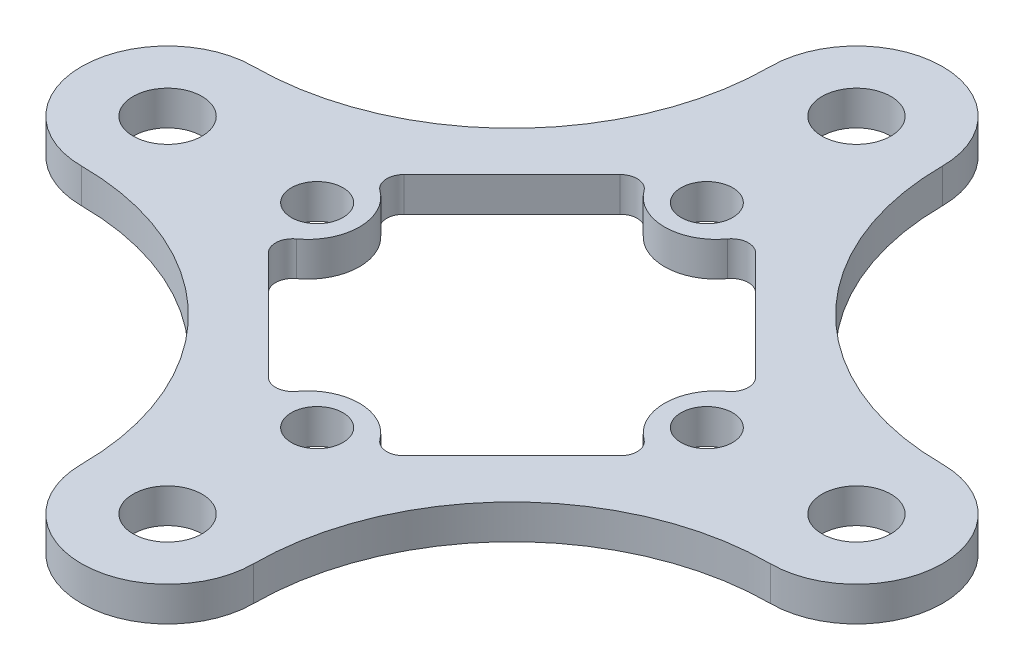
SolidWorks part; units mm, degrees
ref_plane "Front Plane" through (0, 0, 0) normal (0, 0, 1) x (1, 0, 0)
ref_plane "Top Plane" through (0, 0, 0) normal (0, 1, 0) x (1, 0, 0)
ref_plane "Right Plane" through (0, 0, 0) normal (1, 0, 0) x (0, 0, -1)
sketch "Sketch1" plane through (0, 0, 0) normal (0, 1, 0) x (1, 0, 0)
  line L0 (0, 25.1487) -> (0, -24.8633) construction
  line L1 (-28.5376, 0) -> (32.8182, 0) construction
  line L4 (0, 25) -> (0, 0)
  line L5 (0, 0) -> (25, 0)
  circle A0 centre (0, 0) radius 20 construction
  circle A6 centre (0, 20) radius 5 construction
  circle A7 centre (20, 0) radius 5 construction
  arc A8 (5, 20) -> (0, 25) centre (0, 20) ccw
  arc A10 (20, 5) -> (25, 0) centre (20, 0) cw
  arc A12 (5, 20) -> (20, 5) centre (20, 20) ccw
  point P8 (0.326, 0)
  point P17 (0, -0.3063)
  dimension "D1" = 40
  dimension "D2" = 10
extrude "Boss-Extrude1" add sketch "Sketch1" along normal blind 2
pattern_circular "CirPattern1" count 4 over 360 about axis through (0, 0, 0) along (0, 1, 0) of "Boss-Extrude1"
sketch "Sketch2" plane through (0, 2, 0) normal (0, 1, 0) x (1, 0, 0)
  line L0 (0, 26.7191) -> (0, -26.0296) construction
  line L1 (-31.2099, 0) -> (38.8403, 0) construction
  line L2 (0, 11.3137) -> (11.3137, 0) construction
  circle A0 centre (0, 11.3137) radius 1.5
  circle A1 centre (0, 20) radius 2
  circle A2 centre (0, 0) radius 11.3137 construction
  circle A3 centre (0, 0) radius 20 construction
  circle A4 centre (11.3137, 0) radius 1.5
  circle A5 centre (20, 0) radius 2
  circle A6 centre (0, -11.3137) radius 1.5
  circle A7 centre (0, -20) radius 2
  circle A8 centre (-11.3137, 0) radius 1.5
  circle A9 centre (-20, 0) radius 2
  point P28 (0, 0)
  dimension "D2" = 3
  dimension "D3" = 4
  dimension "D4" = 40
  dimension "D1" = 16
  dimension "D5" = 4
extrude "Cut-Extrude1" cut sketch "Sketch2" against normal blind 2
sketch "Sketch3" plane through (0, 2, 0) normal (0, 1, 0) x (1, 0, 0)
  line L0 (-11.2127, 2.9294) -> (-2.9294, 11.2127)
  line L1 (2.9294, 11.2127) -> (11.2127, 2.9294)
  line L2 (11.2127, -2.9294) -> (2.9294, -11.2127)
  line L3 (-2.9294, -11.2127) -> (-11.2127, -2.9294)
  line L4 (-27.2779, 0) -> (28.3919, 0) construction
  line L5 (18.1732, 18.1732) -> (-14.9169, -14.9169) construction
  line L6 (-14.8578, 14.8578) -> (15.401, -15.401) construction
  line L7 (0, -36.8504) -> (0, 30.3129) construction
  arc A0 (-2.9294, 11.2127) -> (2.9294, 11.2127) centre (0, 11.8596) ccw
  arc A2 (2.9294, -11.2127) -> (-2.9294, -11.2127) centre (0, -11.8596) ccw
  arc A3 (-11.2127, -2.9294) -> (-11.2127, 2.9294) centre (-11.8596, 0) ccw
  arc A4 (11.2127, -2.9294) -> (11.2127, 2.9294) centre (11.8596, 0) cw
  circle A5 centre (0, 0) radius 11.8596 construction
  point P20 (0, 11.3841)
  point P21 (-12.0514, 0)
  point P22 (0, -11.8596)
  point P24 (-2.9294, 11.2127)
  dimension "D1" = 3
  dimension "D2" = 45
  dimension "D3" = 45
  dimension "D4" = 20
  dimension "D5" = 20
extrude "Cut-Extrude2" cut sketch "Sketch3" against normal blind 2
fillet "Fillet2" radius 1 8 edges at (-11.2127, 1, 2.9294) (-11.2127, 1, -2.9294) (2.9294, 1, 11.2127) (-2.9294, 1, 11.2127) (11.2127, 1, 2.9294) (11.2127, 1, -2.9294) (2.9294, 1, -11.2127) (-2.9294, 1, -11.2127)
